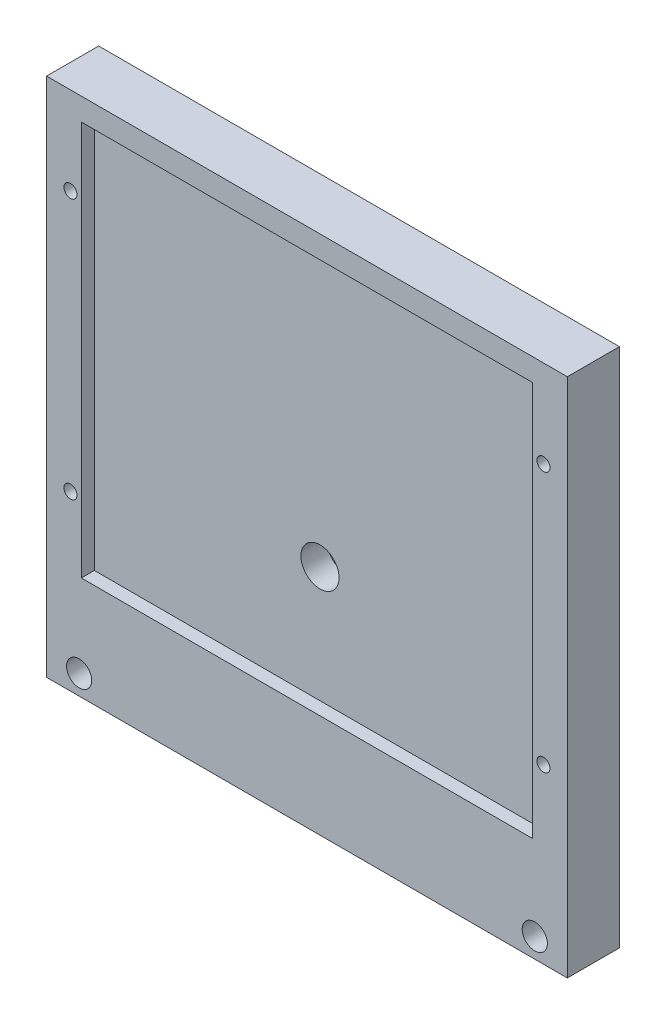
SolidWorks part; units mm, degrees
ref_plane "前视基准面" through (0, 0, 0) normal (0, 0, 1) x (1, 0, 0)
ref_plane "上视基准面" through (0, 0, 0) normal (0, 1, 0) x (1, 0, 0)
ref_plane "右视基准面" through (0, 0, 0) normal (1, 0, 0) x (0, 0, -1)
other "Configuration Table"
sketch "草图1" plane through (0, 0, 0) normal (0, 0, 1) x (1, 0, 0)
  line L1 (-70.2439, 62.0263) -> (49.7561, 62.0263)
  line L2 (-70.2439, 62.0263) -> (-70.2439, -57.9737)
  line L3 (-70.2439, -57.9737) -> (49.7561, -57.9737)
  line L4 (49.7561, 62.0263) -> (49.7561, -57.9737)
  dimension "D1" = 120
  dimension "D2" = 120
extrude "凸台-拉伸1" add sketch "草图1" along normal blind 12
sketch "草图2" plane through (0, 0, 12) normal (0, 0, 1) x (1, 0, 0)
  line L0 (-70.2439, 62.0263) -> (-70.2439, -57.9737) construction
  line L1 (-62.2439, 56.8606) -> (41.7561, 56.8606)
  line L2 (-62.2439, 56.8606) -> (-62.2439, -34.1394)
  line L3 (-62.2439, -34.1394) -> (41.7561, -34.1394)
  line L4 (41.7561, 56.8606) -> (41.7561, -34.1394)
  dimension "D1" = 104
  dimension "D2" = 8
  dimension "D3" = 91
extrude "切除-拉伸1" cut sketch "草图2" against normal blind 3
sketch "草图4" plane through (0, 0, 12) normal (0, 0, 1) x (1, 0, 0)
  line L0 (-62.2439, 56.8606) -> (-62.2439, -34.1394) construction
  circle A0 centre (-10.2439, -7.424) radius 2.25
  circle A1 centre (-64.2376, -53.424) radius 1.75
  dimension "D1" = 52
  dimension "D2" = 46
extrude "切除-拉伸3" cut sketch "草图4" against normal blind 12 contours A0
sketch "草图6" plane through (0, 0, 12) normal (0, 0, 1) x (1, 0, 0)
  circle A0 centre (-62.7439, -53.424) radius 1.75
  circle A1 centre (-10.2439, -7.424) radius 2.25 construction
  circle A2 centre (42.2561, -53.424) radius 1.75
  dimension "D1" = 46
  dimension "D2" = 52.5
  dimension "D3" = 52.5
  dimension "D4" = 46
extrude "切除-拉伸5" cut sketch "草图6" against normal blind 12
sketch "草图7" plane through (0, 0, 12) normal (0, 0, 1) x (1, 0, 0)
  circle A0 centre (-62.7439, -53.424) radius 2.9
  circle A1 centre (42.2561, -53.424) radius 2.9
  circle A2 centre (-10.2439, -7.424) radius 4.4
extrude "切除-拉伸6" cut sketch "草图7" against normal blind 9
sketch "草图8" plane through (0, 0, 12) normal (0, 0, 1) x (1, 0, 0)
  line L0 (-62.2439, -34.1394) -> (41.7561, -34.1394) construction
  line L1 (-62.2439, 56.8606) -> (-62.2439, -34.1394) construction
  line L2 (41.7561, 56.8606) -> (-62.2439, 56.8606) construction
  line L3 (41.7561, 56.8606) -> (-62.2439, 56.8606) construction
  line L4 (41.7561, -34.1394) -> (41.7561, 56.8606) construction
  circle A0 centre (-64.7439, -18.1394) radius 1.5
  circle A1 centre (-64.7439, 41.8606) radius 1.5
  circle A2 centre (44.2561, 41.8606) radius 1.5
  circle A3 centre (44.2561, -18.1394) radius 1.5
  dimension "D1" = 16
  dimension "D2" = 2.5
  dimension "D3" = 15
  dimension "D4" = 2.5
  dimension "D5" = 15
  dimension "D6" = 2.5
extrude "切除-拉伸7" cut sketch "草图8" against normal blind 12
